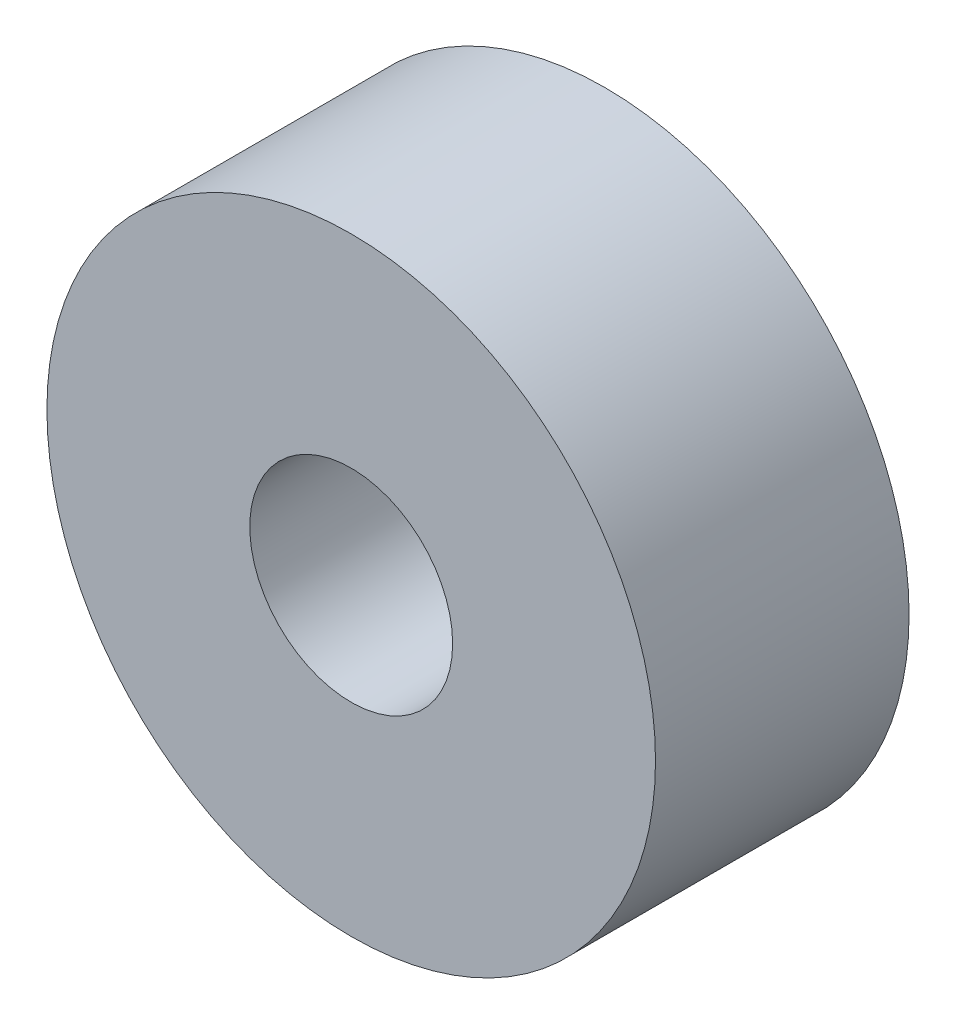
SolidWorks part; units mm, degrees
ref_plane "Plan de face" through (0, 0, 0) normal (0, 0, 1) x (1, 0, 0)
ref_plane "Plan de dessus" through (0, 0, 0) normal (0, 1, 0) x (1, 0, 0)
ref_plane "Plan de droite" through (0, 0, 0) normal (1, 0, 0) x (0, 0, -1)
sketch "Esquisse1" plane through (0, 0, 0) normal (0, 0, 1) x (1, 0, 0)
  circle A0 centre (0, 0) radius 2
  circle A1 centre (0, 0) radius 6
  dimension "D1" = 4
  dimension "D2" = 12
extrude "Boss.-Extru.1" add sketch "Esquisse1" along normal blind 5
